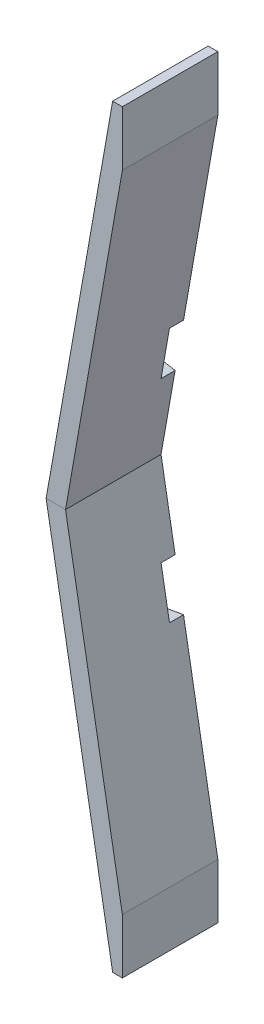
SolidWorks part; units mm, degrees
ref_plane "Front Plane" through (0, 0, 0) normal (0, 0, 1) x (1, 0, 0)
ref_plane "Top Plane" through (0, 0, 0) normal (0, 1, 0) x (1, 0, 0)
ref_plane "Right Plane" through (0, 0, 0) normal (1, 0, 0) x (0, 0, -1)
sketch "Sketch1" plane through (0, 0, 0) normal (0, 0, 1) x (1, 0, 0)
  line L2 (-94.8994, -0.3473) -> (-81.0309, -79)
  line L4 (-92.9298, 0) -> (-90.899, 0)
  line L5 (-92.9298, 0) -> (-94.9607, 0)
  line L6 (-94.8994, -0.3473) -> (-94.9607, 0)
  line L7 (-79, -79) -> (-81.0309, -79)
  line L12 (-90.899, 0) -> (-79, -67.4825)
  line L13 (-79, -67.4825) -> (-79, -79)
extrude "Boss-Extrude1" add sketch "Sketch1" against normal blind 20 contours L2 L7 L13 L12 L4 L5 L6
sketch "Sketch2" plane through (-92.0973, -16.2392, 0) normal (-0.9848, -0.1736, 0) x (0, 0, 1)
  line L0 (-17.06, -11.3403) -> (-22.7216, -11.3403)
  line L4 (-22.7216, -11.3403) -> (-17.06, -11.3403)
  line L5 (-22.7216, -11.3403) -> (-22.7216, -1.1803)
  line L6 (-17.06, -11.3403) -> (-17.06, -1.1803)
  line L9 (-22.7216, -1.1803) -> (-17.06, -1.1803)
  line L10 (-17.06, -11.3403) -> (-17.06, -1.1803)
  line M3 (-20, 16.4897) -> (-20, -63.729)
extrude "Cut-Extrude1" cut sketch "Sketch2" against normal through all contours L9 L0 L6 M3
mirror "Mirror2" about plane through (0, 0, 0) normal (0, 1, 0) of bodies 103
